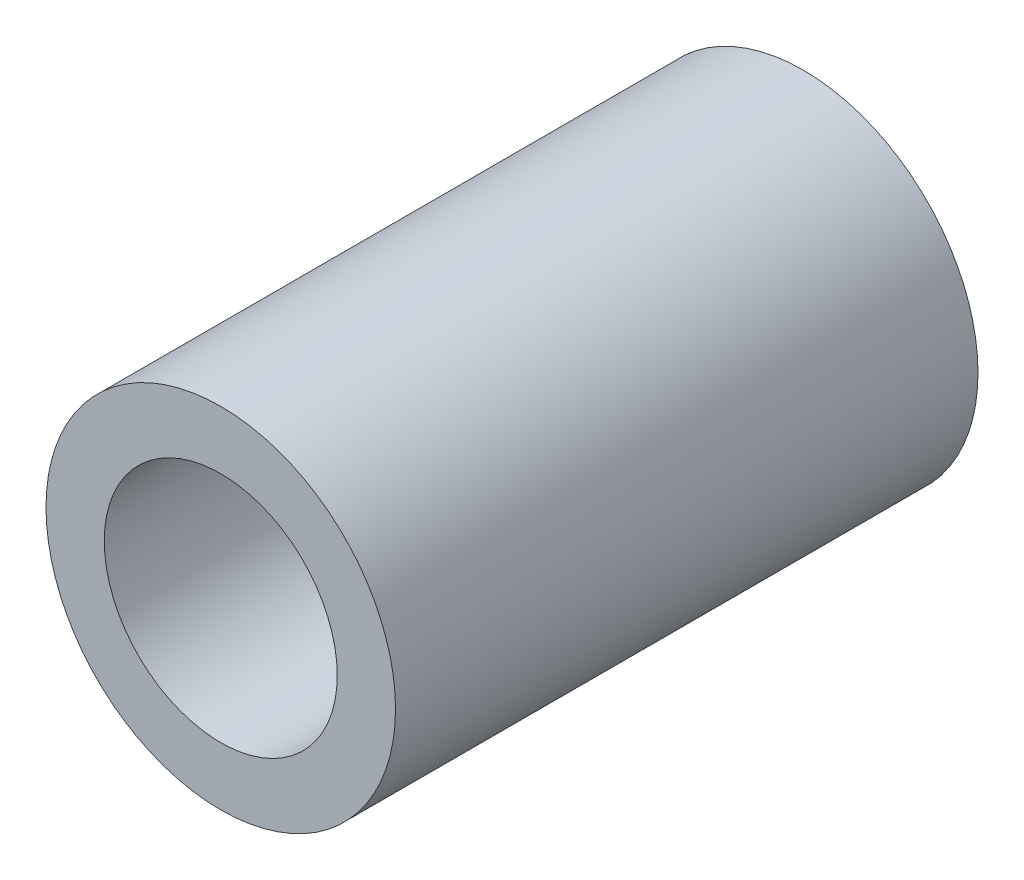
SolidWorks part; units mm, degrees
ref_plane "Front Plane" through (0, 0, 0) normal (0, 0, 1) x (1, 0, 0)
ref_plane "Top Plane" through (0, 0, 0) normal (0, 1, 0) x (1, 0, 0)
ref_plane "Right Plane" through (0, 0, 0) normal (1, 0, 0) x (0, 0, -1)
sketch "Sketch1" plane through (0, 0, 0) normal (0, 0, 1) x (1, 0, 0)
  circle A0 centre (0, 0) radius 3
  circle A1 centre (0, 0) radius 2
  dimension "D1" = 6
  dimension "D2" = 1
extrude "Boss-Extrude1" add sketch "Sketch1" along normal blind 10
